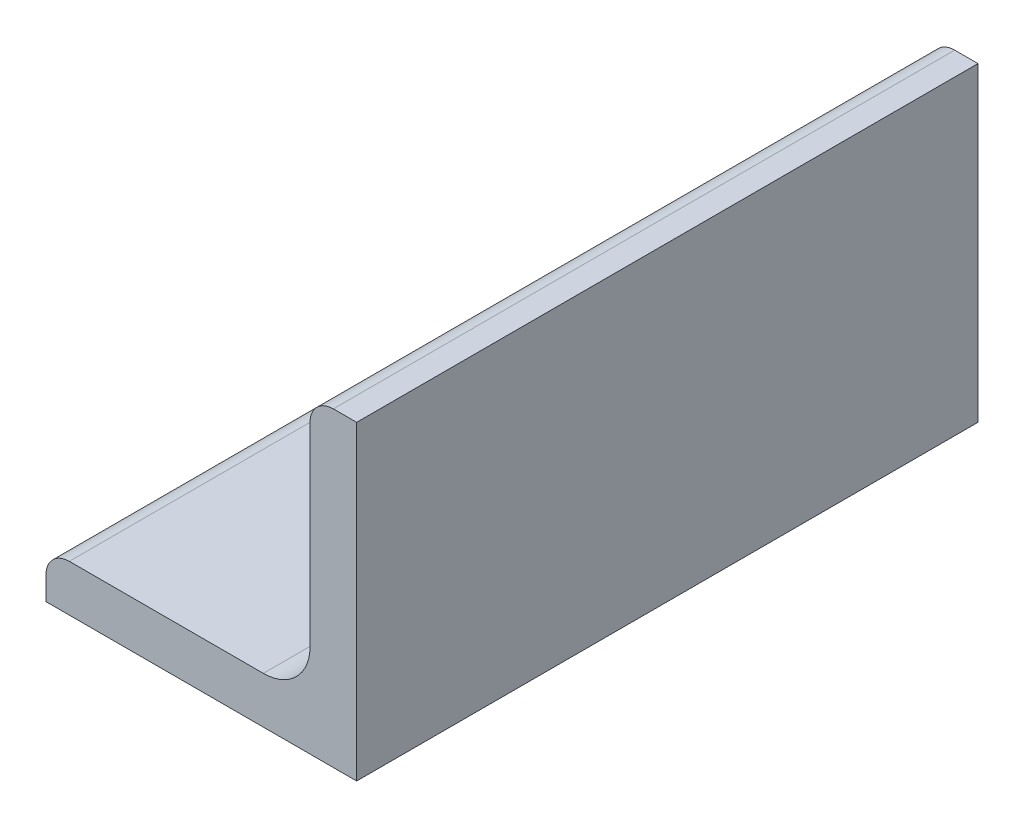
SolidWorks part; units mm, degrees
ref_plane "Front Plane" through (0, 0, 0) normal (0, 0, 1) x (1, 0, 0)
ref_plane "Top Plane" through (0, 0, 0) normal (0, 1, 0) x (1, 0, 0)
ref_plane "Right Plane" through (0, 0, 0) normal (1, 0, 0) x (0, 0, -1)
sketch "Sketch0" plane through (0, 0, 0) normal (0, 0, 1) x (1, 0, 0)
  line L0 (-15.875, -15.875) -> (15.875, -15.875)
  line L1 (15.875, -15.875) -> (15.875, 15.875)
  line L2 (15.875, 0) -> (0, 0) construction
  line L3 (0, 0) -> (0, -15.875) construction
  line L4 (11.1125, -6.3373) -> (11.1125, 15.875) construction
  line L5 (6.3373, -11.1125) -> (-15.875, -11.1125) construction
  arc A0 (11.1125, -6.3373) -> (6.3373, -11.1125) centre (6.3373, -6.3373) cw
  point P3 (9.7139, -9.7139)
  dimension "Inside Corner Radius" = 4.7752
  dimension "Outside Height" = 31.75
  dimension "Inside Height" = 26.9875
  dimension "Inside Width" = 26.9875
  dimension "Wall Thickness" = 4.7625
  dimension "D1" = 4.7625
  dimension "Outside Width" = 31.75
sketch "Sketch1" plane through (0, 0, 0) normal (1, 0, 0) x (0, 0, -1)
  line L0 (152.4, 0) -> (-152.4, 0)
  point P4 (0, 0)
  dimension "Length" = 304.8
sketch "Sketch2" plane through (0, 0, 0) normal (0, 0, 1) x (1, 0, 0)
  line L0 (-15.875, -15.875) -> (15.875, -15.875)
  line L1 (15.875, -15.875) -> (15.875, 15.875)
  line L2 (15.875, 15.875) -> (11.1125, 15.875) construction
  line L3 (11.1125, 13.4938) -> (11.1125, -6.3373)
  line L4 (6.3373, -11.1125) -> (-13.4937, -11.1125)
  line L5 (-15.875, -15.875) -> (-15.875, -11.1125) construction
  line L6 (13.4937, 15.875) -> (15.875, 15.875)
  line L7 (-15.875, -13.4937) -> (-15.875, -15.875)
  line L8 (15.875, 0) -> (0, 0) construction
  line L9 (0, 0) -> (0, -15.875) construction
  arc A0 (11.1125, 13.4938) -> (13.4937, 15.875) centre (13.4937, 13.4938) cw
  arc A1 (-15.875, -13.4937) -> (-13.4937, -11.1125) centre (-13.4937, -13.4937) cw
  arc A2 (11.1125, -6.3373) -> (6.3373, -11.1125) centre (6.3373, -6.3373) cw
  dimension "Inside Radius" = 4.7752
  dimension "Height" = 31.75
  dimension "Width" = 31.75
  dimension "Thickness" = 4.7625
extrude "Boss-Extrude1" add sketch "Sketch2" along normal mid plane 304.8
sketch "Break Locations" plane through (0, 0, 0) normal (1, 0, 0) x (0, 0, -1)
  line L0 (-120.015, 0) -> (120.015, 0)
  line L1 (-152.4, -15.875) -> (-152.4, 15.875) construction
  line L2 (152.4, -15.875) -> (152.4, 15.875) construction
  point P0 (-125.4125, 0)
  point P1 (125.4125, 0)
  point P10 (0, 0)
  point P11 (120.015, 0)
  point P13 (-120.015, 0)
  dimension "D1" = 26.9875
  dimension "D2" = 26.9875
  dimension "D3" = 32.385
sketch "Sketch3" plane through (0, 0, -152.4) normal (0, 0, -1) x (-1, 0, 0)
  line L1 (-15.875, -15.875) -> (16.907, -15.875)
  line L2 (-15.875, -15.875) -> (-15.875, 17.4643)
  line L3 (-15.875, 17.4643) -> (16.907, 17.4643)
  line L4 (16.907, -15.875) -> (16.907, 17.4643)
extrude "Cut-Extrude1" cut sketch "Sketch3" against normal blind 241.3
equation "\"D1@Break Locations\" = .85 * \"Height@Sketch2\""
equation "\"D2@Break Locations\"=\"D1@Break Locations\""
equation "\"Thickness@Sketch2\"=\"wall thickness@sketch0\""
equation "\"Height@Sketch2\"=\"outside height@sketch0\""
equation "\"Width@Sketch2\"=\"outside width@sketch0\""
equation "\"Inside Radius@Sketch2\"=\"inside corner radius@sketch0\""
equation "\"Length@Boss-Extrude1\"=\"length@sketch1\""
equation "\"D3@Break Locations\"=\"D2@Break Locations\"*1.2"
equation "\"D1@Sketch0\"=\"Wall Thickness@Sketch0\""
